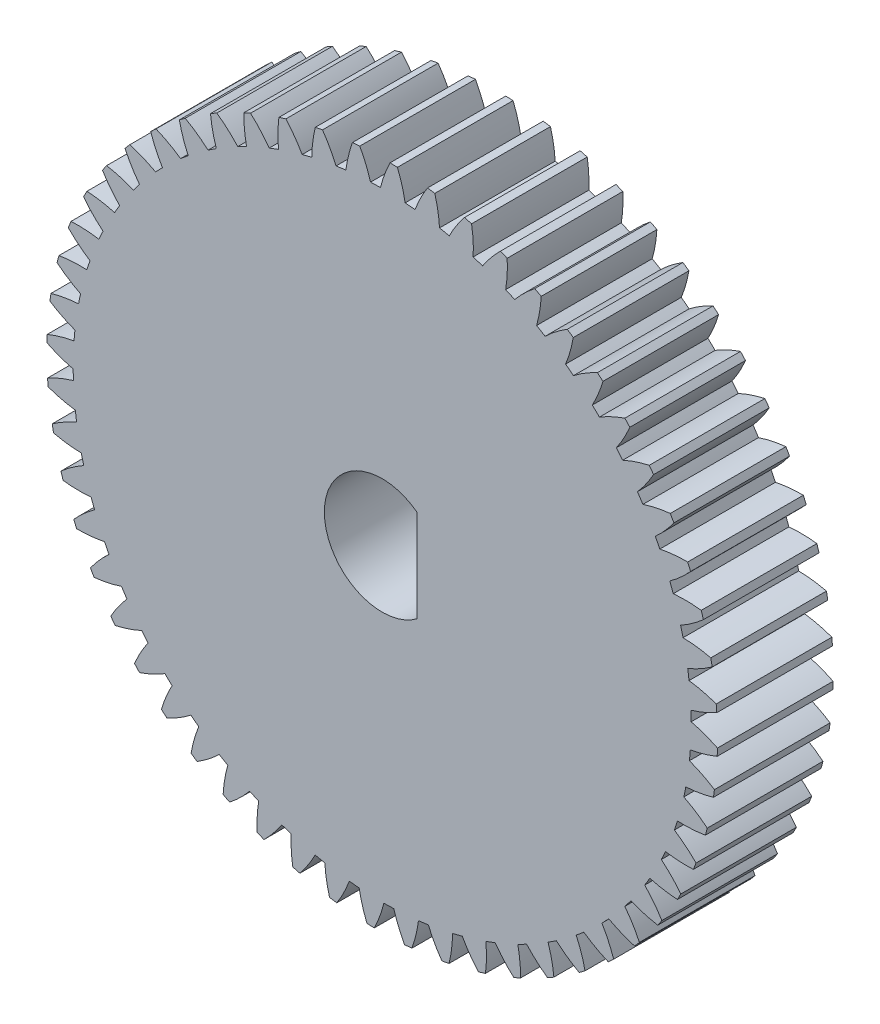
SolidWorks part; units mm, degrees
ref_plane "Front Plane" through (0, 0, 0) normal (0, 0, 1) x (1, 0, 0)
ref_plane "Top Plane" through (0, 0, 0) normal (0, 1, 0) x (1, 0, 0)
ref_plane "Right Plane" through (0, 0, 0) normal (1, 0, 0) x (0, 0, -1)
sketch "Sketch1" plane through (0, 0, 0) normal (0, 0, 1) x (1, 0, 0)
  line L0 (1.905, -2.54) -> (1.905, 2.54)
  arc A0 (1.905, 2.54) -> (1.905, -2.54) centre (0, 0) ccw
  circle B0 centre (0, 0) radius 3.175
  arc B1 (-17.852, 4.5187) -> (-16.5627, 3.6826) centre (-13.3602, 10.0327) ccw
  arc B2 (-16.5627, 3.6826) -> (-16.6723, 3.1497) centre (0, 0) ccw
  arc B3 (-16.6723, 3.1497) -> (-18.1868, 2.89) centre (-16.2344, -3.9488) ccw
  arc B4 (-18.1868, 2.89) -> (-18.2457, 2.4915) centre (0, 0) ccw
  arc B5 (-18.2457, 2.4915) -> (-16.8709, 1.805) centre (-14.3995, 8.4737) ccw
  arc B6 (-16.8709, 1.805) -> (-16.9201, 1.2632) centre (0, 0) ccw
  arc B7 (-16.9201, 1.2632) -> (-18.396, 0.8355) centre (-15.6902, -5.7416) ccw
  arc B8 (-18.396, 0.8355) -> (-18.4099, 0.433) centre (0, 0) ccw
  arc B9 (-18.4099, 0.433) -> (-16.9669, -0.0953) centre (-15.2577, 6.8082) ccw
  arc B10 (-16.9669, -0.0953) -> (-16.9552, -0.6392) centre (0, 0) ccw
  arc B11 (-16.9552, -0.6392) -> (-18.3739, -1.2294) centre (-14.9487, -7.4623) ccw
  arc B12 (-18.3739, -1.2294) -> (-18.3426, -1.631) centre (0, 0) ccw
  arc B13 (-18.3426, -1.631) -> (-16.8496, -1.9944) centre (-15.924, 5.0571) ccw
  arc B14 (-16.8496, -1.9944) -> (-16.777, -2.5335) centre (0, 0) ccw
  arc B15 (-16.777, -2.5335) -> (-18.1207, -3.2789) centre (-14.0192, -9.0891) ccw
  arc B16 (-18.1207, -3.2789) -> (-18.0447, -3.6745) centre (0, 0) ccw
  arc B17 (-18.0447, -3.6745) -> (-16.5203, -3.8684) centre (-16.3901, 3.2424) ccw
  arc B18 (-16.5203, -3.8684) -> (-16.3878, -4.396) centre (0, 0) ccw
  arc B19 (-16.3878, -4.396) -> (-17.6397, -5.2872) centre (-12.9134, -10.6016) ccw
  arc B20 (-17.6397, -5.2872) -> (-17.5198, -5.6717) centre (0, 0) ccw
  arc B21 (-17.5198, -5.6717) -> (-15.9833, -5.6938) centre (-16.6501, 1.3869) ccw
  arc B22 (-15.9833, -5.6938) -> (-15.7926, -6.2032) centre (0, 0) ccw
  arc B23 (-15.7926, -6.2032) -> (-16.9368, -7.229) centre (-11.6452, -11.9807) ccw
  arc B24 (-16.9368, -7.229) -> (-16.7746, -7.5977) centre (0, 0) ccw
  arc B25 (-16.7746, -7.5977) -> (-15.2453, -7.4476) centre (-16.7007, -0.4861) ccw
  arc B26 (-15.2453, -7.4476) -> (-14.9987, -7.9324) centre (0, 0) ccw
  arc B27 (-14.9987, -7.9324) -> (-16.0209, -9.0798) centre (-10.2305, -13.2093) ccw
  arc B28 (-16.0209, -9.0798) -> (-15.8185, -9.4281) centre (0, 0) ccw
  arc B29 (-15.8185, -9.4281) -> (-14.3156, -9.1077) centre (-16.5412, -2.3529) ccw
  arc B30 (-14.3156, -9.1077) -> (-14.0163, -9.5619) centre (0, 0) ccw
  arc B31 (-14.0163, -9.5619) -> (-14.9035, -10.8165) centre (-8.6872, -14.2717) ccw
  arc B32 (-14.9035, -10.8165) -> (-14.6634, -11.1399) centre (0, 0) ccw
  arc B33 (-14.6634, -11.1399) -> (-13.2059, -10.6532) centre (-16.1738, -4.1901) ccw
  arc B34 (-13.2059, -10.6532) -> (-12.8576, -11.0711) centre (0, 0) ccw
  arc B35 (-12.8576, -11.0711) -> (-13.5988, -12.4172) centre (-7.0347, -15.1546) ccw
  arc B36 (-13.5988, -12.4172) -> (-13.3239, -12.7116) centre (0, 0) ccw
  arc B37 (-13.3239, -12.7116) -> (-11.93, -12.0648) centre (-15.6029, -5.9747) ccw
  arc B38 (-11.93, -12.0648) -> (-11.5371, -12.4411) centre (0, 0) ccw
  arc B39 (-11.5371, -12.4411) -> (-12.123, -13.8617) centre (-5.2937, -15.8469) ccw
  arc B40 (-12.123, -13.8617) -> (-11.8169, -14.1235) centre (0, 0) ccw
  arc B41 (-11.8169, -14.1235) -> (-10.5042, -13.3247) centre (-14.8359, -7.6841) ccw
  arc B42 (-10.5042, -13.3247) -> (-10.0716, -13.6546) centre (0, 0) ccw
  arc B43 (-10.0716, -13.6546) -> (-10.4947, -15.1318) centre (-3.4861, -16.34) ccw
  arc B44 (-10.4947, -15.1318) -> (-10.1613, -15.3578) centre (0, 0) ccw
  arc B45 (-10.1613, -15.3578) -> (-8.9462, -14.417) centre (-13.8823, -9.2968) ccw
  arc B46 (-8.9462, -14.417) -> (-8.4795, -14.6964) centre (0, 0) ccw
  arc B47 (-8.4795, -14.6964) -> (-8.7345, -16.2117) centre (-1.6347, -16.6276) ccw
  arc B48 (-8.7345, -16.2117) -> (-8.3779, -16.3989) centre (0, 0) ccw
  arc B49 (-8.3779, -16.3989) -> (-7.2758, -15.328) centre (-12.7541, -10.7927) ccw
  arc B50 (-7.2758, -15.328) -> (-6.7807, -15.5534) centre (0, 0) ccw
  arc B51 (-6.7807, -15.5534) -> (-6.8645, -17.0878) centre (0.2373, -16.706) ccw
  arc B52 (-6.8645, -17.0878) -> (-6.4891, -17.2338) centre (0, 0) ccw
  arc B53 (-6.4891, -17.2338) -> (-5.5139, -16.0463) centre (-11.4655, -12.1528) ccw
  arc B54 (-5.5139, -16.0463) -> (-4.9966, -16.2148) centre (0, 0) ccw
  arc B55 (-4.9966, -16.2148) -> (-4.9081, -17.7489) centre (2.1063, -16.5744) ccw
  arc B56 (-4.9081, -17.7489) -> (-4.5187, -17.852) centre (0, 0) ccw
  arc B57 (-4.5187, -17.852) -> (-3.6826, -16.5627) centre (-10.0327, -13.3602) ccw
  arc B58 (-3.6826, -16.5627) -> (-3.1497, -16.6723) centre (0, 0) ccw
  arc B59 (-3.1497, -16.6723) -> (-2.89, -18.1868) centre (3.9488, -16.2344) ccw
  arc B60 (-2.89, -18.1868) -> (-2.4915, -18.2457) centre (0, 0) ccw
  arc B61 (-2.4915, -18.2457) -> (-1.805, -16.8709) centre (-8.4737, -14.3995) ccw
  arc B62 (-1.805, -16.8709) -> (-1.2632, -16.9201) centre (0, 0) ccw
  arc B63 (-1.2632, -16.9201) -> (-0.8355, -18.396) centre (5.7416, -15.6902) ccw
  arc B64 (-0.8355, -18.396) -> (-0.433, -18.4099) centre (0, 0) ccw
  arc B65 (-0.433, -18.4099) -> (0.0953, -16.9669) centre (-6.8082, -15.2577) ccw
  arc B66 (0.0953, -16.9669) -> (0.6392, -16.9552) centre (0, 0) ccw
  arc B67 (0.6392, -16.9552) -> (1.2294, -18.3739) centre (7.4623, -14.9487) ccw
  arc B68 (1.2294, -18.3739) -> (1.631, -18.3426) centre (0, 0) ccw
  arc B69 (1.631, -18.3426) -> (1.9944, -16.8496) centre (-5.0571, -15.924) ccw
  arc B70 (1.9944, -16.8496) -> (2.5335, -16.777) centre (0, 0) ccw
  arc B71 (2.5335, -16.777) -> (3.2789, -18.1207) centre (9.0891, -14.0192) ccw
  arc B72 (3.2789, -18.1207) -> (3.6745, -18.0447) centre (0, 0) ccw
  arc B73 (3.6745, -18.0447) -> (3.8684, -16.5203) centre (-3.2424, -16.3901) ccw
  arc B74 (3.8684, -16.5203) -> (4.396, -16.3878) centre (0, 0) ccw
  arc B75 (4.396, -16.3878) -> (5.2872, -17.6397) centre (10.6016, -12.9134) ccw
  arc B76 (5.2872, -17.6397) -> (5.6717, -17.5198) centre (0, 0) ccw
  arc B77 (5.6717, -17.5198) -> (5.6938, -15.9833) centre (-1.3869, -16.6501) ccw
  arc B78 (5.6938, -15.9833) -> (6.2032, -15.7926) centre (0, 0) ccw
  arc B79 (6.2032, -15.7926) -> (7.229, -16.9368) centre (11.9807, -11.6452) ccw
  arc B80 (7.229, -16.9368) -> (7.5977, -16.7746) centre (0, 0) ccw
  arc B81 (7.5977, -16.7746) -> (7.4476, -15.2453) centre (0.4861, -16.7007) ccw
  arc B82 (7.4476, -15.2453) -> (7.9324, -14.9987) centre (0, 0) ccw
  arc B83 (7.9324, -14.9987) -> (9.0798, -16.0209) centre (13.2093, -10.2305) ccw
  arc B84 (9.0798, -16.0209) -> (9.4281, -15.8185) centre (0, 0) ccw
  arc B85 (9.4281, -15.8185) -> (9.1077, -14.3156) centre (2.3529, -16.5412) ccw
  arc B86 (9.1077, -14.3156) -> (9.5619, -14.0163) centre (0, 0) ccw
  arc B87 (9.5619, -14.0163) -> (10.8165, -14.9035) centre (14.2717, -8.6872) ccw
  arc B88 (10.8165, -14.9035) -> (11.1399, -14.6634) centre (0, 0) ccw
  arc B89 (11.1399, -14.6634) -> (10.6532, -13.2059) centre (4.1901, -16.1738) ccw
  arc B90 (10.6532, -13.2059) -> (11.0711, -12.8576) centre (0, 0) ccw
  arc B91 (11.0711, -12.8576) -> (12.4172, -13.5988) centre (15.1546, -7.0347) ccw
  arc B92 (12.4172, -13.5988) -> (12.7116, -13.3239) centre (0, 0) ccw
  arc B93 (12.7116, -13.3239) -> (12.0648, -11.93) centre (5.9747, -15.6029) ccw
  arc B94 (12.0648, -11.93) -> (12.4411, -11.5371) centre (0, 0) ccw
  arc B95 (12.4411, -11.5371) -> (13.8617, -12.123) centre (15.8469, -5.2937) ccw
  arc B96 (13.8617, -12.123) -> (14.1235, -11.8169) centre (0, 0) ccw
  arc B97 (14.1235, -11.8169) -> (13.3247, -10.5042) centre (7.6841, -14.8359) ccw
  arc B98 (13.3247, -10.5042) -> (13.6546, -10.0716) centre (0, 0) ccw
  arc B99 (13.6546, -10.0716) -> (15.1318, -10.4947) centre (16.34, -3.4861) ccw
  arc B100 (15.1318, -10.4947) -> (15.3578, -10.1613) centre (0, 0) ccw
  arc B101 (15.3578, -10.1613) -> (14.417, -8.9462) centre (9.2968, -13.8823) ccw
  arc B102 (14.417, -8.9462) -> (14.6964, -8.4795) centre (0, 0) ccw
  arc B103 (14.6964, -8.4795) -> (16.2117, -8.7345) centre (16.6276, -1.6347) ccw
  arc B104 (16.2117, -8.7345) -> (16.3989, -8.3779) centre (0, 0) ccw
  arc B105 (16.3989, -8.3779) -> (15.328, -7.2758) centre (10.7927, -12.7541) ccw
  arc B106 (15.328, -7.2758) -> (15.5534, -6.7807) centre (0, 0) ccw
  arc B107 (15.5534, -6.7807) -> (17.0878, -6.8645) centre (16.706, 0.2373) ccw
  arc B108 (17.0878, -6.8645) -> (17.2338, -6.4891) centre (0, 0) ccw
  arc B109 (17.2338, -6.4891) -> (16.0463, -5.5139) centre (12.1528, -11.4655) ccw
  arc B110 (16.0463, -5.5139) -> (16.2148, -4.9966) centre (0, 0) ccw
  arc B111 (16.2148, -4.9966) -> (17.7489, -4.9081) centre (16.5744, 2.1063) ccw
  arc B112 (17.7489, -4.9081) -> (17.852, -4.5187) centre (0, 0) ccw
  arc B113 (17.852, -4.5187) -> (16.5627, -3.6826) centre (13.3602, -10.0327) ccw
  arc B114 (16.5627, -3.6826) -> (16.6723, -3.1497) centre (0, 0) ccw
  arc B115 (16.6723, -3.1497) -> (18.1868, -2.89) centre (16.2344, 3.9488) ccw
  arc B116 (18.1868, -2.89) -> (18.2457, -2.4915) centre (0, 0) ccw
  arc B117 (18.2457, -2.4915) -> (16.8709, -1.805) centre (14.3995, -8.4737) ccw
  arc B118 (16.8709, -1.805) -> (16.9201, -1.2632) centre (0, 0) ccw
  arc B119 (16.9201, -1.2632) -> (18.396, -0.8355) centre (15.6902, 5.7416) ccw
  arc B120 (18.396, -0.8355) -> (18.4099, -0.433) centre (0, 0) ccw
  arc B121 (18.4099, -0.433) -> (16.9669, 0.0953) centre (15.2577, -6.8082) ccw
  arc B122 (16.9669, 0.0953) -> (16.9552, 0.6392) centre (0, 0) ccw
  arc B123 (16.9552, 0.6392) -> (18.3739, 1.2294) centre (14.9487, 7.4623) ccw
  arc B124 (18.3739, 1.2294) -> (18.3426, 1.631) centre (0, 0) ccw
  arc B125 (18.3426, 1.631) -> (16.8496, 1.9944) centre (15.924, -5.0571) ccw
  arc B126 (16.8496, 1.9944) -> (16.777, 2.5335) centre (0, 0) ccw
  arc B127 (16.777, 2.5335) -> (18.1207, 3.2789) centre (14.0192, 9.0891) ccw
  arc B128 (18.1207, 3.2789) -> (18.0447, 3.6745) centre (0, 0) ccw
  arc B129 (18.0447, 3.6745) -> (16.5203, 3.8684) centre (16.3901, -3.2424) ccw
  arc B130 (16.5203, 3.8684) -> (16.3878, 4.396) centre (0, 0) ccw
  arc B131 (16.3878, 4.396) -> (17.6397, 5.2872) centre (12.9134, 10.6016) ccw
  arc B132 (17.6397, 5.2872) -> (17.5198, 5.6717) centre (0, 0) ccw
  arc B133 (17.5198, 5.6717) -> (15.9833, 5.6938) centre (16.6501, -1.3869) ccw
  arc B134 (15.9833, 5.6938) -> (15.7926, 6.2032) centre (0, 0) ccw
  arc B135 (15.7926, 6.2032) -> (16.9368, 7.229) centre (11.6452, 11.9807) ccw
  arc B136 (16.9368, 7.229) -> (16.7746, 7.5977) centre (0, 0) ccw
  arc B137 (16.7746, 7.5977) -> (15.2453, 7.4476) centre (16.7007, 0.4861) ccw
  arc B138 (15.2453, 7.4476) -> (14.9987, 7.9324) centre (0, 0) ccw
  arc B139 (14.9987, 7.9324) -> (16.0209, 9.0798) centre (10.2305, 13.2093) ccw
  arc B140 (16.0209, 9.0798) -> (15.8185, 9.4281) centre (0, 0) ccw
  arc B141 (15.8185, 9.4281) -> (14.3156, 9.1077) centre (16.5412, 2.3529) ccw
  arc B142 (14.3156, 9.1077) -> (14.0163, 9.5619) centre (0, 0) ccw
  arc B143 (14.0163, 9.5619) -> (14.9035, 10.8165) centre (8.6872, 14.2717) ccw
  arc B144 (14.9035, 10.8165) -> (14.6634, 11.1399) centre (0, 0) ccw
  arc B145 (14.6634, 11.1399) -> (13.2059, 10.6532) centre (16.1738, 4.1901) ccw
  arc B146 (13.2059, 10.6532) -> (12.8576, 11.0711) centre (0, 0) ccw
  arc B147 (12.8576, 11.0711) -> (13.5988, 12.4172) centre (7.0347, 15.1546) ccw
  arc B148 (13.5988, 12.4172) -> (13.3239, 12.7116) centre (0, 0) ccw
  arc B149 (13.3239, 12.7116) -> (11.93, 12.0648) centre (15.6029, 5.9747) ccw
  arc B150 (11.93, 12.0648) -> (11.5371, 12.4411) centre (0, 0) ccw
  arc B151 (11.5371, 12.4411) -> (12.123, 13.8617) centre (5.2937, 15.8469) ccw
  arc B152 (12.123, 13.8617) -> (11.8169, 14.1235) centre (0, 0) ccw
  arc B153 (11.8169, 14.1235) -> (10.5042, 13.3247) centre (14.8359, 7.6841) ccw
  arc B154 (10.5042, 13.3247) -> (10.0716, 13.6546) centre (0, 0) ccw
  arc B155 (10.0716, 13.6546) -> (10.4947, 15.1318) centre (3.4861, 16.34) ccw
  arc B156 (10.4947, 15.1318) -> (10.1613, 15.3578) centre (0, 0) ccw
  arc B157 (10.1613, 15.3578) -> (8.9462, 14.417) centre (13.8823, 9.2968) ccw
  arc B158 (8.9462, 14.417) -> (8.4795, 14.6964) centre (0, 0) ccw
  arc B159 (8.4795, 14.6964) -> (8.7345, 16.2117) centre (1.6347, 16.6276) ccw
  arc B160 (8.7345, 16.2117) -> (8.3779, 16.3989) centre (0, 0) ccw
  arc B161 (8.3779, 16.3989) -> (7.2758, 15.328) centre (12.7541, 10.7927) ccw
  arc B162 (7.2758, 15.328) -> (6.7807, 15.5534) centre (0, 0) ccw
  arc B163 (6.7807, 15.5534) -> (6.8645, 17.0878) centre (-0.2373, 16.706) ccw
  arc B164 (6.8645, 17.0878) -> (6.4891, 17.2338) centre (0, 0) ccw
  arc B165 (6.4891, 17.2338) -> (5.5139, 16.0463) centre (11.4655, 12.1528) ccw
  arc B166 (5.5139, 16.0463) -> (4.9966, 16.2148) centre (0, 0) ccw
  arc B167 (4.9966, 16.2148) -> (4.9081, 17.7489) centre (-2.1063, 16.5744) ccw
  arc B168 (4.9081, 17.7489) -> (4.5187, 17.852) centre (0, 0) ccw
  arc B169 (4.5187, 17.852) -> (3.6826, 16.5627) centre (10.0327, 13.3602) ccw
  arc B170 (3.6826, 16.5627) -> (3.1497, 16.6723) centre (0, 0) ccw
  arc B171 (3.1497, 16.6723) -> (2.89, 18.1868) centre (-3.9488, 16.2344) ccw
  arc B172 (2.89, 18.1868) -> (2.4915, 18.2457) centre (0, 0) ccw
  arc B173 (2.4915, 18.2457) -> (1.805, 16.8709) centre (8.4737, 14.3995) ccw
  arc B174 (1.805, 16.8709) -> (1.2632, 16.9201) centre (0, 0) ccw
  arc B175 (1.2632, 16.9201) -> (0.8355, 18.396) centre (-5.7416, 15.6902) ccw
  arc B176 (0.8355, 18.396) -> (0.433, 18.4099) centre (0, 0) ccw
  arc B177 (0.433, 18.4099) -> (-0.0953, 16.9669) centre (6.8082, 15.2577) ccw
  arc B178 (-0.0953, 16.9669) -> (-0.6392, 16.9552) centre (0, 0) ccw
  arc B179 (-0.6392, 16.9552) -> (-1.2294, 18.3739) centre (-7.4623, 14.9487) ccw
  arc B180 (-1.2294, 18.3739) -> (-1.631, 18.3426) centre (0, 0) ccw
  arc B181 (-1.631, 18.3426) -> (-1.9944, 16.8496) centre (5.0571, 15.924) ccw
  arc B182 (-1.9944, 16.8496) -> (-2.5335, 16.777) centre (0, 0) ccw
  arc B183 (-2.5335, 16.777) -> (-3.2789, 18.1207) centre (-9.0891, 14.0192) ccw
  arc B184 (-3.2789, 18.1207) -> (-3.6745, 18.0447) centre (0, 0) ccw
  arc B185 (-3.6745, 18.0447) -> (-3.8684, 16.5203) centre (3.2424, 16.3901) ccw
  arc B186 (-3.8684, 16.5203) -> (-4.396, 16.3878) centre (0, 0) ccw
  arc B187 (-4.396, 16.3878) -> (-5.2872, 17.6397) centre (-10.6016, 12.9134) ccw
  arc B188 (-5.2872, 17.6397) -> (-5.6717, 17.5198) centre (0, 0) ccw
  arc B189 (-5.6717, 17.5198) -> (-5.6938, 15.9833) centre (1.3869, 16.6501) ccw
  arc B190 (-5.6938, 15.9833) -> (-6.2032, 15.7926) centre (0, 0) ccw
  arc B191 (-6.2032, 15.7926) -> (-7.229, 16.9368) centre (-11.9807, 11.6452) ccw
  arc B192 (-7.229, 16.9368) -> (-7.5977, 16.7746) centre (0, 0) ccw
  arc B193 (-7.5977, 16.7746) -> (-7.4476, 15.2453) centre (-0.4861, 16.7007) ccw
  arc B194 (-7.4476, 15.2453) -> (-7.9324, 14.9987) centre (0, 0) ccw
  arc B195 (-7.9324, 14.9987) -> (-9.0798, 16.0209) centre (-13.2093, 10.2305) ccw
  arc B196 (-9.0798, 16.0209) -> (-9.4281, 15.8185) centre (0, 0) ccw
  arc B197 (-9.4281, 15.8185) -> (-9.1077, 14.3156) centre (-2.3529, 16.5412) ccw
  arc B198 (-9.1077, 14.3156) -> (-9.5619, 14.0163) centre (0, 0) ccw
  arc B199 (-9.5619, 14.0163) -> (-10.8165, 14.9035) centre (-14.2717, 8.6872) ccw
  arc B200 (-10.8165, 14.9035) -> (-11.1399, 14.6634) centre (0, 0) ccw
  arc B201 (-11.1399, 14.6634) -> (-10.6532, 13.2059) centre (-4.1901, 16.1738) ccw
  arc B202 (-10.6532, 13.2059) -> (-11.0711, 12.8576) centre (0, 0) ccw
  arc B203 (-11.0711, 12.8576) -> (-12.4172, 13.5988) centre (-15.1546, 7.0347) ccw
  arc B204 (-12.4172, 13.5988) -> (-12.7116, 13.3239) centre (0, 0) ccw
  arc B205 (-12.7116, 13.3239) -> (-12.0648, 11.93) centre (-5.9747, 15.6029) ccw
  arc B206 (-12.0648, 11.93) -> (-12.4411, 11.5371) centre (0, 0) ccw
  arc B207 (-12.4411, 11.5371) -> (-13.8617, 12.123) centre (-15.8469, 5.2937) ccw
  arc B208 (-13.8617, 12.123) -> (-14.1235, 11.8169) centre (0, 0) ccw
  arc B209 (-14.1235, 11.8169) -> (-13.3247, 10.5042) centre (-7.6841, 14.8359) ccw
  arc B210 (-13.3247, 10.5042) -> (-13.6546, 10.0716) centre (0, 0) ccw
  arc B211 (-13.6546, 10.0716) -> (-15.1318, 10.4947) centre (-16.34, 3.4861) ccw
  arc B212 (-15.1318, 10.4947) -> (-15.3578, 10.1613) centre (0, 0) ccw
  arc B213 (-15.3578, 10.1613) -> (-14.417, 8.9462) centre (-9.2968, 13.8823) ccw
  arc B214 (-14.417, 8.9462) -> (-14.6964, 8.4795) centre (0, 0) ccw
  arc B215 (-14.6964, 8.4795) -> (-16.2117, 8.7345) centre (-16.6276, 1.6347) ccw
  arc B216 (-16.2117, 8.7345) -> (-16.3989, 8.3779) centre (0, 0) ccw
  arc B217 (-16.3989, 8.3779) -> (-15.328, 7.2758) centre (-10.7927, 12.7541) ccw
  arc B218 (-15.328, 7.2758) -> (-15.5534, 6.7807) centre (0, 0) ccw
  arc B219 (-15.5534, 6.7807) -> (-17.0878, 6.8645) centre (-16.706, -0.2373) ccw
  arc B220 (-17.0878, 6.8645) -> (-17.2338, 6.4891) centre (0, 0) ccw
  arc B221 (-17.2338, 6.4891) -> (-16.0463, 5.5139) centre (-12.1528, 11.4655) ccw
  arc B222 (-16.0463, 5.5139) -> (-16.2148, 4.9966) centre (0, 0) ccw
  arc B223 (-16.2148, 4.9966) -> (-17.7489, 4.9081) centre (-16.5744, -2.1063) ccw
  arc B224 (-17.7489, 4.9081) -> (-17.852, 4.5187) centre (0, 0) ccw
  dimension "D1" = 1.905
sketch_block_instance "Motor_Gear-1"
sketch_block "Motor_Gear"
extrude "Boss-Extrude1" add sketch "Sketch1" along normal blind 6.35 contours B223 B224 B1 B2 B3 B4 B5 B6 B7 B8 B9 B10 B11 B12 B13 B14 B15 B16 B17 B18 B19 B20 B21 B22 B23 B24 B25 B26 B27 B28 B29 B30 B31 B32 B33 B34 B35 B36 B37 B38 B39 B40 B41 B42 B43 B44 B45 B46 B47 B48 B49 | L0 B0 | L0 A0
